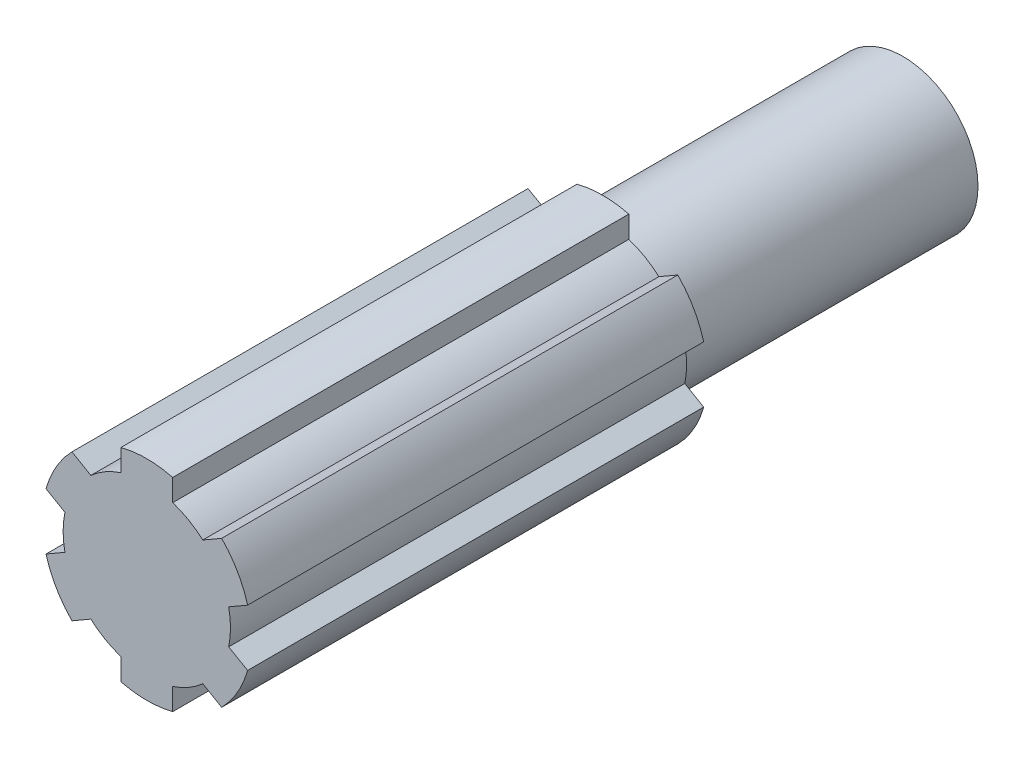
SolidWorks part; units mm, degrees
ref_plane "Front Plane" through (0, 0, 0) normal (0, 0, 1) x (1, 0, 0)
ref_plane "Top Plane" through (0, 0, 0) normal (0, 1, 0) x (1, 0, 0)
ref_plane "Right Plane" through (0, 0, 0) normal (1, 0, 0) x (0, 0, -1)
sketch "Sketch1" plane through (0, 0, 0) normal (0, 0, 1) x (1, 0, 0)
  circle A0 centre (0, 0) radius 12.5
  dimension "D1" = 25
extrude "Boss-Extrude1" add sketch "Sketch1" along normal blind 50
sketch "Sketch2" plane through (0, 0, 50) normal (0, 0, 1) x (1, 0, 0)
  line L0 (9.3226, 10.3707) -> (12.4773, 12.1921)
  line L1 (16.7973, 4.7096) -> (13.6426, 2.8883)
  line L2 (-4.32, 16.9016) -> (-4.32, 13.259) construction
  line L3 (4.32, 16.9016) -> (4.32, 13.259) construction
  line L4 (-4.32, 13.259) -> (-4.32, 16.9016)
  line L5 (4.32, 16.9016) -> (4.32, 13.259)
  line L7 (13.6426, -2.8883) -> (16.7973, -4.7096)
  line L8 (12.4773, -12.1921) -> (9.3226, -10.3707)
  line L9 (4.32, -13.259) -> (4.32, -16.9016)
  line L10 (-4.32, -16.9016) -> (-4.32, -13.259)
  line L11 (-9.3226, -10.3707) -> (-12.4773, -12.1921)
  line L12 (-16.7973, -4.7096) -> (-13.6426, -2.8883)
  line L13 (-13.6426, 2.8883) -> (-16.7973, 4.7096)
  line L14 (-12.4773, 12.1921) -> (-9.3226, 10.3707)
  arc A0 (-12.4773, 12.1921) -> (-16.7973, 4.7096) centre (0, 0) ccw
  arc A1 (-13.6426, 2.8883) -> (-13.6426, -2.8883) centre (0, 0) ccw
  arc A2 (4.32, 16.9016) -> (-4.32, 16.9016) centre (0, 0) ccw
  arc A3 (16.7973, 4.7096) -> (12.4773, 12.1921) centre (0, 0) ccw
  arc A4 (12.4773, -12.1921) -> (16.7973, -4.7096) centre (0, 0) ccw
  arc A5 (-4.32, -16.9016) -> (4.32, -16.9016) centre (0, 0) ccw
  arc A6 (-16.7973, -4.7096) -> (-12.4773, -12.1921) centre (0, 0) ccw
  arc A7 (-4.32, 13.259) -> (-9.3226, 10.3707) centre (0, 0) ccw
  arc A8 (9.3226, 10.3707) -> (4.32, 13.259) centre (0, 0) ccw
  arc A9 (13.6426, -2.8883) -> (13.6426, 2.8883) centre (0, 0) ccw
  arc A10 (4.32, -13.259) -> (9.3226, -10.3707) centre (0, 0) ccw
  arc A11 (-9.3226, -10.3707) -> (-4.32, -13.259) centre (0, 0) ccw
  point P9 (0, 15.5798)
  dimension "D1" = 34.89
  dimension "D2" = 27.89
  dimension "D3" = 6
extrude "Boss-Extrude2" add sketch "Sketch2" along normal blind 76
